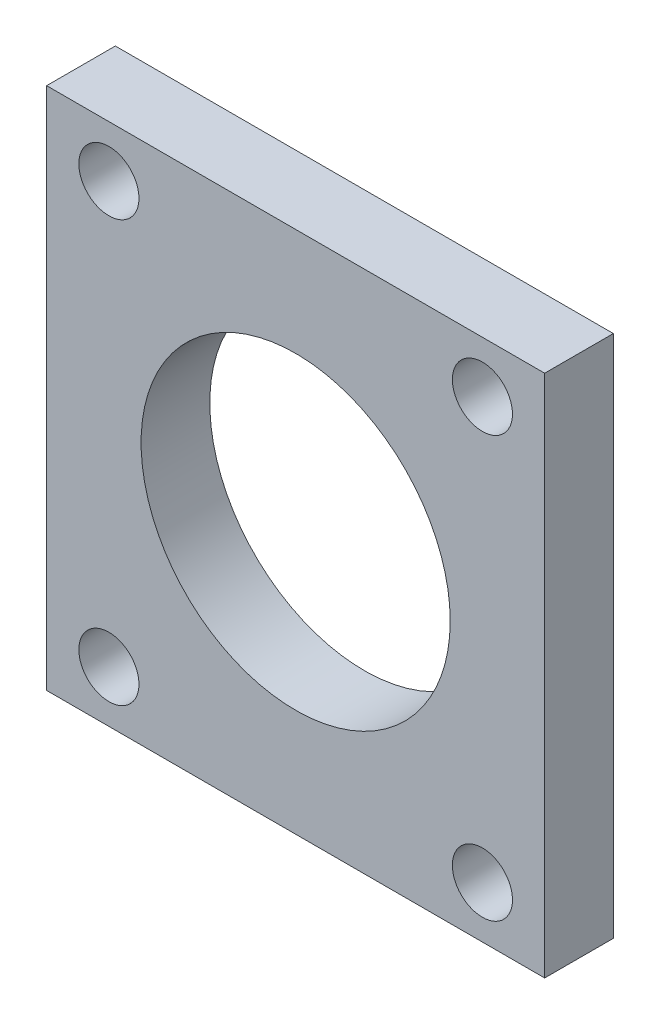
SolidWorks part; units mm, degrees
ref_plane "Front Plane" through (0, 0, 0) normal (0, 0, 1) x (1, 0, 0)
ref_plane "Top Plane" through (0, 0, 0) normal (0, 1, 0) x (1, 0, 0)
ref_plane "Right Plane" through (0, 0, 0) normal (1, 0, 0) x (0, 0, -1)
sketch "Sketch1" plane through (0, 0, 0) normal (0, 0, 1) x (1, 0, 0)
  line L0 (-346.832, -9.5) -> (-404.832, -9.5) construction
  line L1 (-404.832, -40) -> (-346.832, -40)
  line L2 (-404.832, -40) -> (-404.832, 21)
  line L3 (-404.832, 21) -> (-346.832, 21)
  line L4 (-346.832, -40) -> (-346.832, 21)
  line L5 (-404.832, -40) -> (-346.832, 21) construction
  line L6 (-404.832, 21) -> (-346.832, -40) construction
  circle A1 centre (-375.832, -9.5) radius 18
  dimension "D1" = 61
  dimension "D2" = 36
  dimension "D3" = 58
extrude "Boss-Extrude1" add sketch "Sketch1" along normal blind 8
fillet "Fillet1" [suppressed] radius 2
extrude "Cut-Extrude24" cut sketch "Sketch25" against normal blind 20
sketch "Sketch25" plane through (-362.1139, -45.1919, 10) normal (0, 0, 1) x (1, 0, 0)
  line L0 (15.2819, 35.6919) -> (-42.7181, 35.6919) construction
  line L1 (15.2819, 7.1919) -> (15.2819, 64.1919) construction
  line L2 (-42.7181, 7.1919) -> (-42.7181, 64.1919) construction
  line L3 (-13.7181, 66.1919) -> (-13.7181, 5.1919) construction
  line L4 (-40.7181, 66.1919) -> (13.2819, 66.1919) construction
  line L5 (-40.7181, 5.1919) -> (13.2819, 5.1919) construction
  circle A2 centre (-34.7181, 11.1919) radius 4.05
  circle A3 centre (-35.4681, 60.1919) radius 4.05
  circle A5 centre (7.2819, 11.1919) radius 4.05
  circle A8 centre (8.0319, 60.1919) radius 4.05
  dimension "D3" = 8.1
  dimension "D1" = 8
  dimension "D2" = 6
extrude "Cut-Extrude25" cut sketch "Sketch26" against normal blind 80
sketch "Sketch26" plane through (-392.7222, 41.5814, 68) normal (0, 0, 1) x (-1, 0, 0)
  circle A0 centre (-16.8901, 51.0814) radius 12.25
  circle A1 centre (-38.6401, 75.5814) radius 3.5
  circle A2 centre (4.8599, 75.5814) radius 3.5
  circle A3 centre (-38.6401, 26.5814) radius 3.5
  circle A4 centre (4.8599, 26.5814) radius 3.5
  circle A5 centre (-16.8901, 16.1218) radius 2.7
